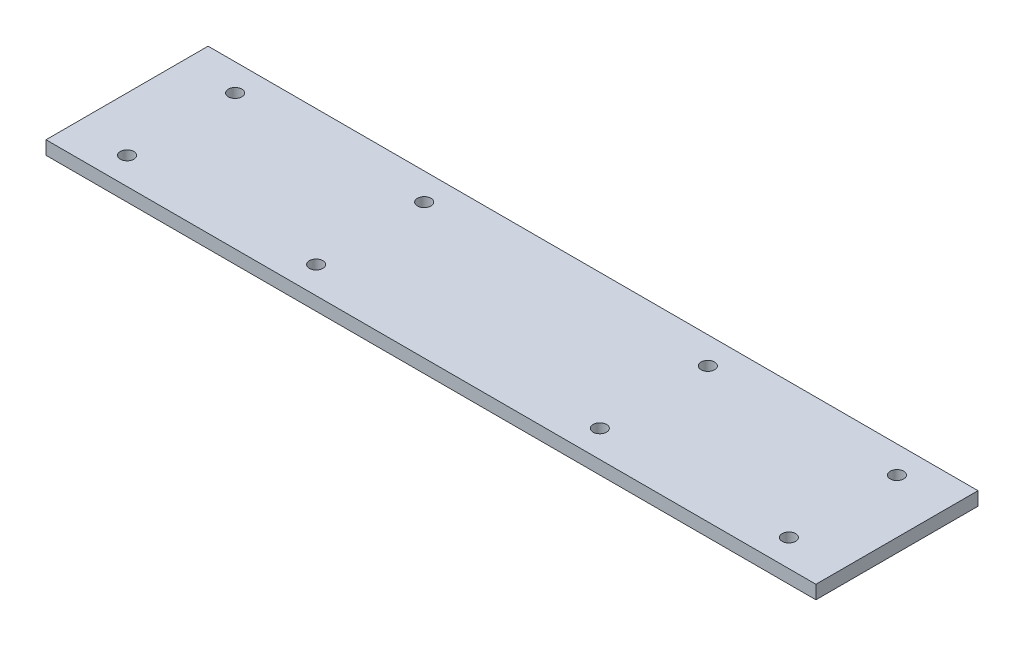
SolidWorks part; units mm, degrees
material "Cast Carbon Steel"
ref_plane "Front Plane" through (0, 0, 0) normal (0, 0, 1) x (1, 0, 0)
ref_plane "Top Plane" through (0, 0, 0) normal (0, 1, 0) x (1, 0, 0)
ref_plane "Right Plane" through (0, 0, 0) normal (1, 0, 0) x (0, 0, -1)
sketch "Sketch1" plane through (0, 0, 0) normal (0, 1, 0) x (1, 0, 0)
  line L1 (-295.5989, 152.4) -> (428.3011, 152.4)
  line L2 (-295.5989, 152.4) -> (-295.5989, 0)
  line L3 (-295.5989, 0) -> (428.3011, 0)
  line L4 (428.3011, 152.4) -> (428.3011, 0)
  dimension "D1" = 723.9
  dimension "D2" = 152.4
  dimension "D3" = 0
  dimension "D4" = 295.5989
extrude "Boss-Extrude1" add sketch "Sketch1" along normal blind 12.7
sketch "Sketch2" plane through (0, 12.7, 0) normal (0, 1, 0) x (1, 0, 0)
  line L0 (428.3011, 0) -> (428.3011, 152.4) construction
  line L1 (66.3511, 152.4) -> (66.3511, 0) construction
  line L2 (428.3011, 152.4) -> (-295.5989, 152.4) construction
  line L3 (-295.5989, 0) -> (428.3011, 0) construction
  circle A0 centre (377.5011, 127) radius 6.35
  circle A1 centre (377.5011, 25.4) radius 6.35
  circle A2 centre (199.7011, 127) radius 6.35
  circle A3 centre (199.7011, 25.4) radius 6.35
  circle A4 centre (-244.7989, 127) radius 6.35
  circle A5 centre (-66.9989, 127) radius 6.35
  circle A6 centre (-244.7989, 25.4) radius 6.35
  circle A7 centre (-66.9989, 25.4) radius 6.35
  dimension "D1" = 12.7
  dimension "D2" = 12.7
  dimension "D3" = 12.7
  dimension "D4" = 12.7
  dimension "D5" = 50.8
  dimension "D6" = 25.4
  dimension "D7" = 25.4
  dimension "D8" = 177.8
extrude "Cut-Extrude1" cut sketch "Sketch2" against normal through all
